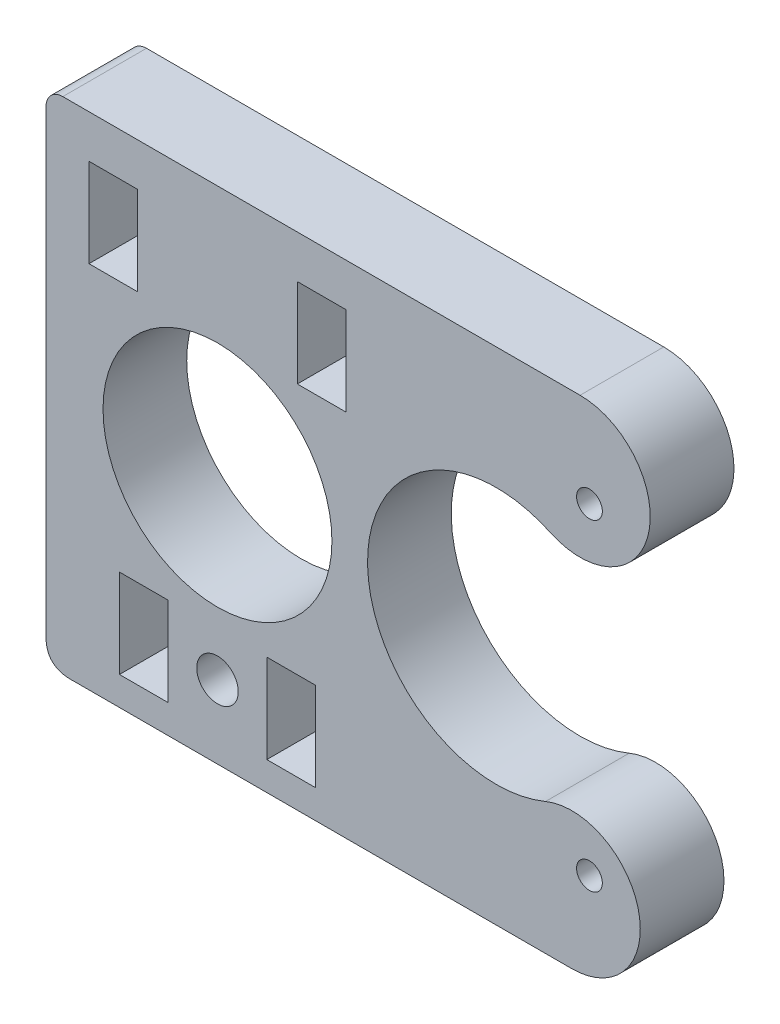
SolidWorks part; units mm, degrees
ref_plane "Front Plane" through (0, 0, 0) normal (0, 0, 1) x (1, 0, 0)
ref_plane "Top Plane" through (0, 0, 0) normal (0, 1, 0) x (1, 0, 0)
ref_plane "Right Plane" through (0, 0, 0) normal (1, 0, 0) x (0, 0, -1)
sketch "Sketch1" plane through (0, 0, 0) normal (0, 0, 1) x (1, 0, 0)
  line L0 (669.2168, 349.1462) -> (647.9164, 349.1462)
  line L1 (646.7465, 347.9762) -> (646.7465, 315.8353)
  line L2 (648.7733, 314.1462) -> (669.2168, 314.1462)
  line L3 (653.1465, 339.9462) -> (653.1465, 346.1462)
  line L4 (653.1465, 346.1462) -> (649.7465, 346.1462)
  line L5 (649.7465, 346.1462) -> (649.7465, 339.9462)
  line L6 (649.7465, 339.9462) -> (653.1465, 339.9462)
  line L7 (651.8765, 316.1462) -> (655.2765, 316.1462)
  line L8 (655.2765, 316.1462) -> (655.2765, 322.3462)
  line L9 (655.2765, 322.3462) -> (651.8765, 322.3462)
  line L10 (651.8765, 322.3462) -> (651.8765, 316.1462)
  line L11 (667.7065, 339.9462) -> (667.7065, 346.1462)
  line L12 (667.7065, 346.1462) -> (664.3065, 346.1462)
  line L13 (664.3065, 346.1462) -> (664.3065, 339.9462)
  line L14 (664.3065, 339.9462) -> (667.7065, 339.9462)
  line L15 (662.1765, 322.3462) -> (662.1765, 316.1462)
  line L16 (662.1765, 316.1462) -> (665.5765, 316.1462)
  line L17 (665.5765, 316.1462) -> (665.5765, 322.3462)
  line L18 (665.5765, 322.3462) -> (662.1765, 322.3462)
  line L19 (-318.4867, 331.6462) -> (49681.5133, 331.6462) construction
  line L20 (669.2168, -651.3598) -> (669.2168, 49348.6402) construction
  line L21 (653.1465, 339.9462) -> (664.3065, 339.9462) construction
  line L22 (657.2765, 319.2462) -> (655.2765, 319.2462) construction
  line L23 (660.1765, 319.2462) -> (662.1765, 319.2462) construction
  line L24 (658.7265, -666.0306) -> (658.7265, 49333.9694) construction
  line L25 (669.2168, 314.1462) -> (683.4935, 314.1462)
  line L26 (669.2168, 349.1462) -> (684.0705, 349.1462)
  line L27 (684.7265, 320.3962) -> (684.7265, 331.6462) construction
  line L28 (684.7265, 331.6462) -> (684.7265, 342.8962) construction
  line L29 (684.7265, -669.0722) -> (684.7265, 49330.9278) construction
  line L30 (662.1765, 331.6462) -> (662.1765, 349.1462) construction
  line L31 (662.1765, 331.6462) -> (662.1765, 314.1462) construction
  circle A0 centre (684.7265, 342.8962) radius 0.8999
  circle A1 centre (684.7265, 320.3962) radius 0.8999
  arc A2 (681.9988, 339.7926) -> (684.0705, 349.1462) centre (684.0705, 344.2399) ccw
  circle A3 centre (658.7265, 319.2462) radius 1.45
  arc A4 (646.7465, 347.9762) -> (647.9164, 349.1462) centre (647.9164, 347.9762) cw
  arc A5 (683.4935, 314.1462) -> (681.6557, 323.3485) centre (683.4935, 318.9309) ccw
  circle A8 centre (658.7265, 331.6462) radius 8
  arc A10 (681.9988, 339.7926) -> (681.6557, 323.3485) centre (678.2038, 331.6462) ccw
  spline S7 degree 2 poles (646.7465, 315.8353) (646.7465, 314.0272) (648.7733, 314.1462) knots 0 0 0 1 1 1
  point P27 (658.7265, 339.9462)
  dimension "D5" = 2.9
  dimension "D12" = 26
  dimension "D1" = 2
  dimension "D2" = 6.2
  dimension "D3" = 3.4
  dimension "D4" = 3.4
  dimension "D6" = 11.16
  dimension "D7" = 3
  dimension "D8" = 3
  dimension "D9" = 2
  dimension "D10" = 30
  dimension "D11" = 11.25
extrude "Boss-Extrude2" add sketch "Sketch1" along normal blind 5.85
